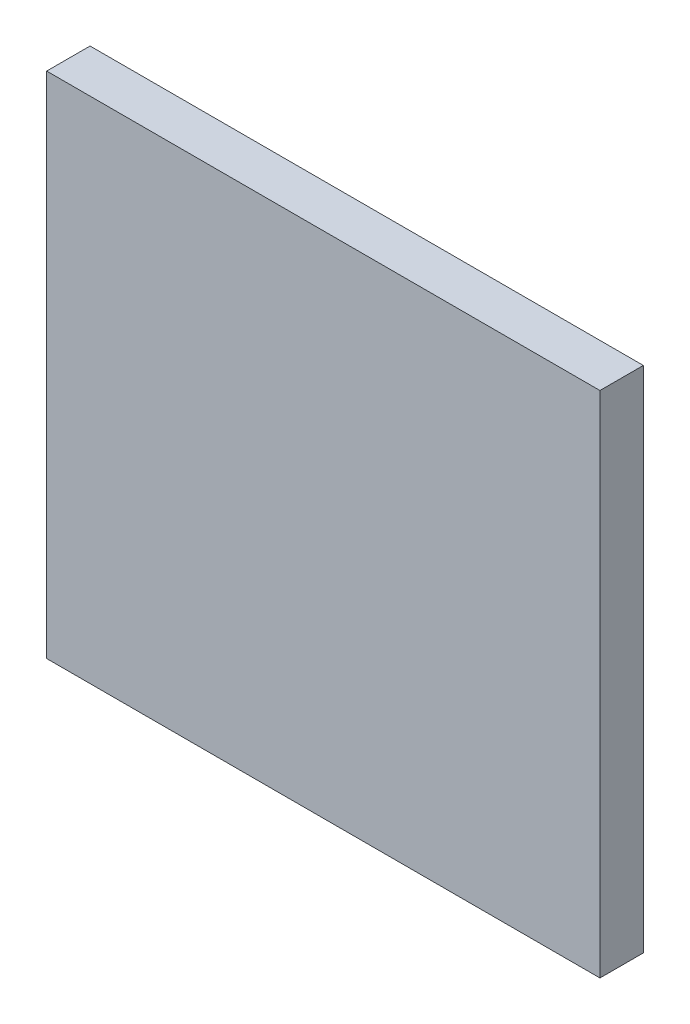
SolidWorks part; units mm, degrees
ref_plane "Спереди" through (0, 0, 0) normal (0, 0, 1) x (1, 0, 0)
ref_plane "Сверху" through (0, 0, 0) normal (0, 1, 0) x (1, 0, 0)
ref_plane "Справа" through (0, 0, 0) normal (1, 0, 0) x (0, 0, -1)
sketch "Эскиз1" plane through (0, 0, 0) normal (0, 0, 1) x (1, 0, 0)
  line L1 (182.8284, -106.4605) -> (157.3284, -106.4605)
  line L2 (182.8284, -106.4605) -> (182.8284, -83.0105)
  line L3 (182.8284, -83.0105) -> (157.3284, -83.0105)
  line L4 (157.3284, -106.4605) -> (157.3284, -83.0105)
  dimension "D1" = 25.5
  dimension "D2" = 23.45
extrude "Бобышка-Вытянуть1" add sketch "Эскиз1" along normal blind 2
